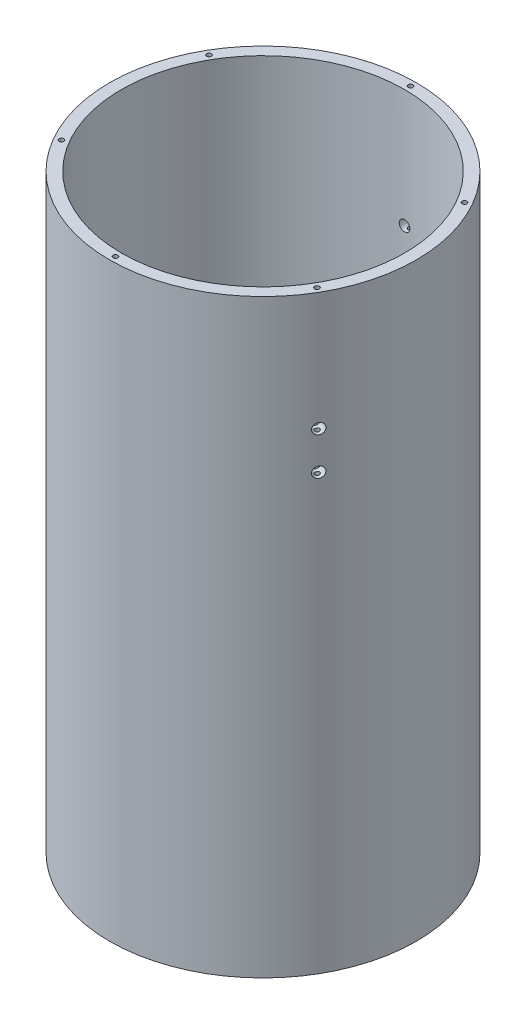
SolidWorks part; units mm, degrees
ref_plane "Plan de face" through (0, 0, 0) normal (0, 0, 1) x (1, 0, 0)
ref_plane "Plan de dessus" through (0, 0, 0) normal (0, 1, 0) x (1, 0, 0)
ref_plane "Plan de droite" through (0, 0, 0) normal (1, 0, 0) x (0, 0, -1)
sketch "Esquisse1" plane through (0, 0, 0) normal (0, 1, 0) x (1, 0, 0)
  circle A0 centre (0, 0) radius 65
extrude "Boss.-Extru.1" add sketch "Esquisse1" along normal blind 250
sketch "Esquisse2" plane through (0, 250, 0) normal (0, 1, 0) x (1, 0, 0)
  circle A0 centre (0, 0) radius 60
extrude "Enlèv. mat.-Extru.1" cut sketch "Esquisse2" against normal blind 250
sketch "Esquisse7" plane through (0, 250, 0) normal (0, 1, 0) x (1, 0, 0)
  circle A3 centre (-54.1266, 31.25) radius 1
  circle A4 centre (-54.1266, -31.25) radius 1
  circle A5 centre (0, -62.5) radius 1
  circle A6 centre (54.1266, -31.25) radius 1
  circle A7 centre (54.1266, 31.25) radius 1
  circle A8 centre (0, 62.5) radius 1
extrude "Enlèv. mat.-Extru.2" cut sketch "Esquisse7" against normal through all
hole_wizard "Dégagement M41" positions "Esquisse3D4" profile "Esquisse11" hole size "M4" standard "ISO"
sketch3d "Esquisse3D4"
  point P2 (0, 200, -65)
sketch "Esquisse11" plane through (0, 200, -65) normal (1, 0, 0) x (0, 1, 0)
  line L0 (0, 0) -> (0, 21.3519)
  line L1 (0, 21.3519) -> (2.25, 20)
  line L2 (2.25, 20) -> (2.25, 0)
  line L5 (2.25, 0) -> (0, 0)
  line L10 (0, 21.3519) -> (-2.25, 20) construction
  line L11 (0, -6.35) -> (0, 107.95) construction
  dimension "Diamètre du perçage" = 4.5
  dimension "Profondeur du perçage" = 20
  dimension "Angle de pointe" = 118
hole_wizard "Dégagement M42" positions "Esquisse3D5" profile "Esquisse12" hole size "M4" standard "ISO"
sketch3d "Esquisse3D5"
  point P0 (0, 184, -65)
sketch "Esquisse12" plane through (0, 184, -65) normal (1, 0, 0) x (0, 1, 0)
  line L0 (0, 0) -> (0, 21.3519)
  line L1 (0, 21.3519) -> (2.25, 20)
  line L2 (2.25, 20) -> (2.25, 0)
  line L5 (2.25, 0) -> (0, 0)
  line L10 (0, 21.3519) -> (-2.25, 20) construction
  line L11 (0, -6.35) -> (0, 107.95) construction
  dimension "Diamètre du perçage" = 4.5
  dimension "Profondeur du perçage" = 20
  dimension "Angle de pointe" = 118
hole_wizard "Dégagement M44" positions "Esquisse3D7" profile "Esquisse14" hole size "M4" standard "ISO"
sketch3d "Esquisse3D7"
  point P0 (56.2338, 200, 32.6)
  point P2 (56.2338, 184, 32.6)
sketch "Esquisse14" plane through (56.2338, 200, 32.6) normal (0, 1, 0) x (0.5015, 0, -0.8651)
  line L0 (0, 0) -> (0, 21.3519)
  line L1 (0, 21.3519) -> (2.25, 20)
  line L2 (2.25, 20) -> (2.25, 0)
  line L5 (2.25, 0) -> (0, 0)
  line L10 (0, 21.3519) -> (-2.25, 20) construction
  line L11 (0, -6.35) -> (0, 107.95) construction
  dimension "Diamètre du perçage" = 4.5
  dimension "Profondeur du perçage" = 20
  dimension "Angle de pointe" = 118
hole_wizard "Dégagement M45" positions "Esquisse3D8" profile "Esquisse15" hole size "M4" standard "ISO"
sketch3d "Esquisse3D8"
  point P0 (-56.2338, 200, 32.6)
  point P2 (-56.2338, 184, 32.6)
sketch "Esquisse15" plane through (-56.2338, 200, 32.6) normal (0, 1, 0) x (0.5015, 0, 0.8651)
  line L0 (0, 0) -> (0, 21.3519)
  line L1 (0, 21.3519) -> (2.25, 20)
  line L2 (2.25, 20) -> (2.25, 0)
  line L5 (2.25, 0) -> (0, 0)
  line L10 (0, 21.3519) -> (-2.25, 20) construction
  line L11 (0, -6.35) -> (0, 107.95) construction
  dimension "Diamètre du perçage" = 4.5
  dimension "Profondeur du perçage" = 20
  dimension "Angle de pointe" = 118
sketch "Esquisse16" plane through (0, 250, 0) normal (0, 1, 0) x (1, 0, 0)
